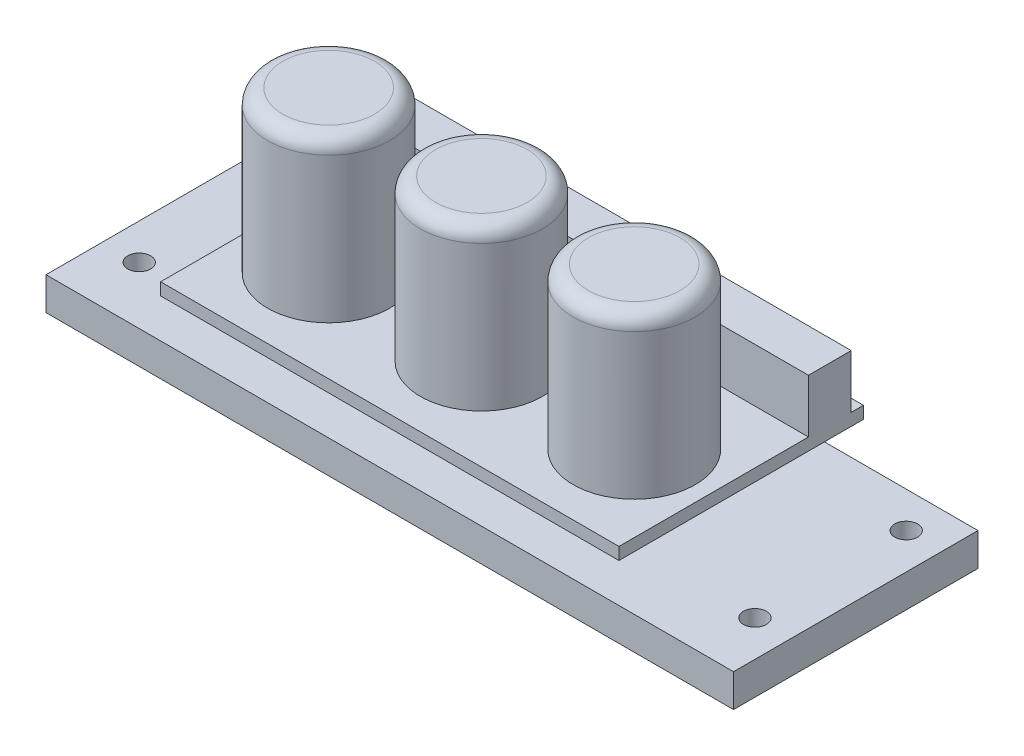
SolidWorks part; units mm, degrees
ref_plane "Front Plane" through (0, 0, 0) normal (0, 0, 1) x (1, 0, 0)
ref_plane "Top Plane" through (0, 0, 0) normal (0, 1, 0) x (1, 0, 0)
ref_plane "Right Plane" through (0, 0, 0) normal (1, 0, 0) x (0, 0, -1)
sketch "Sketch2" plane through (0, 0, 0) normal (0, 1, 0) x (1, 0, 0)
  line L0 (0, -55) -> (0, 55) construction
  line L1 (-45, -16) -> (45, -16)
  line L2 (-45, -16) -> (-45, 16)
  line L3 (-45, 16) -> (45, 16)
  line L4 (45, -16) -> (45, 16)
  line L5 (-45, -16) -> (45, 16) construction
  line L6 (-45, 16) -> (45, -16) construction
  circle A0 centre (40.3, 11.3) radius 1.5
  circle A1 centre (40.3, -8.5) radius 1.5
  circle A2 centre (-40.3, -8.5) radius 1.5
  circle A3 centre (-40.3, 11.3) radius 1.5
  point P0 (0, 0)
  dimension "D3" = 3
  dimension "D1" = 90
  dimension "D2" = 32
  dimension "D4" = 4.7
  dimension "D5" = 4.7
  dimension "D6" = 19.8
extrude "Boss-Extrude1" add sketch "Sketch2" along normal blind 4.3
ref_plane "Plane1" through (0, 9.4, 0) normal (0, 1, 0) x (1, 0, 0)
sketch "Sketch3" plane through (0, 9.4, 0) normal (0, 1, 0) x (1, 0, 0)
  line L0 (45, 16) -> (-45, 16) construction
  line L1 (-30, -16) -> (30, -16)
  line L2 (-30, -16) -> (-30, 16)
  line L3 (-30, 16) -> (30, 16)
  line L4 (30, -16) -> (30, 16)
  line L5 (-30, -16) -> (30, 16) construction
  line L6 (-30, 16) -> (30, -16) construction
  point P0 (0, 0)
  dimension "D1" = 60
extrude "Boss-Extrude2" add sketch "Sketch3" along normal blind 1.6 separate body
sketch "Sketch4" plane through (0, 11, 0) normal (0, 1, 0) x (1, 0, 0)
  line L1 (-30, -16) -> (30, -16) construction
  line L2 (0, -6.05) -> (0, 6.05) construction
  circle A0 centre (20, -4) radius 8
  circle A1 centre (0, -4) radius 8
  circle A2 centre (-20, -4) radius 8
  dimension "D1" = 16
  dimension "D4" = 16
  dimension "D2" = 12
  dimension "D3" = 20
extrude "Boss-Extrude3" add sketch "Sketch4" along normal blind 21
fillet "Fillet1" radius 2 3 edges at (-20, 32, -4) (20, 32, 12) (0, 32, 12)
sketch "Sketch5" plane through (0, 0, 0) normal (1, 0, 0) x (0, 0, -1)
  line L5 (14.4072, 11) -> (8.8072, 11)
  line L6 (14.4072, 11) -> (14.4072, 18)
  line L7 (8.8072, 11) -> (8.8072, 18)
  line L8 (14.4072, 18) -> (8.8072, 18)
  line L9 (-16, 11) -> (16, 11) construction
  dimension "D1" = 5.6
  dimension "D2" = 7
extrude "Boss-Extrude4" add sketch "Sketch5" along normal blind 30 and the other way blind 30 contours L6 L8 L7 L5
